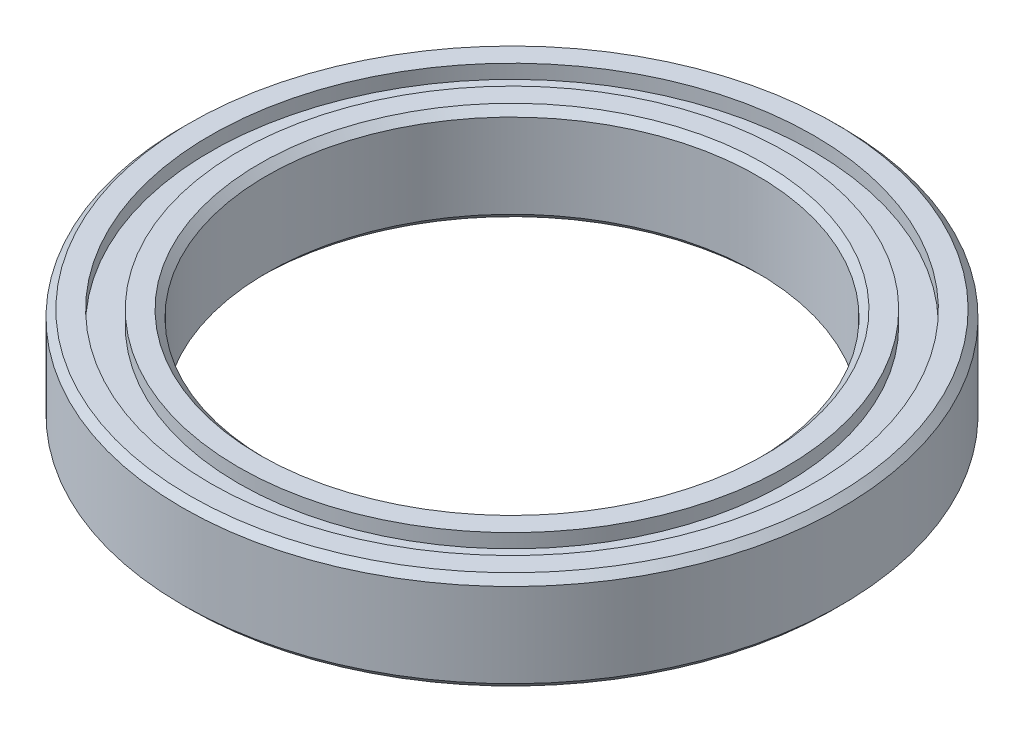
SolidWorks part; units mm, degrees
ref_plane "Front Plane" through (0, 0, 0) normal (0, 0, 1) x (1, 0, 0)
ref_plane "Top Plane" through (0, 0, 0) normal (0, 1, 0) x (1, 0, 0)
ref_plane "Right Plane" through (0, 0, 0) normal (1, 0, 0) x (0, 0, -1)
sketch "Sketch1" plane through (0, 0, 0) normal (0, 1, 0) x (1, 0, 0)
  circle A0 centre (0, 0) radius 23.5
  circle A1 centre (0, 0) radius 17.5
  dimension "D1" = 47
  dimension "D2" = 35
extrude "Boss-Extrude1" add sketch "Sketch1" along normal blind 7
sketch "Sketch2" plane through (0, 7, 0) normal (0, 1, 0) x (1, 0, 0)
  circle A0 centre (0, 0) radius 19.5
  circle A1 centre (0, 0) radius 21.5
  dimension "D1" = 39
  dimension "D2" = 43
extrude "Cut-Extrude1" cut sketch "Sketch2" against normal blind 1
sketch "Sketch3" plane through (0, 0, 0) normal (0, -1, 0) x (1, 0, 0)
  circle A0 centre (0, 0) radius 19.5
  circle A1 centre (0, 0) radius 21.5
  dimension "D1" = 39
  dimension "D2" = 43
extrude "Cut-Extrude2" cut sketch "Sketch3" against normal blind 1
chamfer "Chamfer1" distance 0.5 angle 45 4 edges at (0, 7, 17.5) (0, 7, 23.5) (0, 0, 17.5) (0, 0, 23.5)
